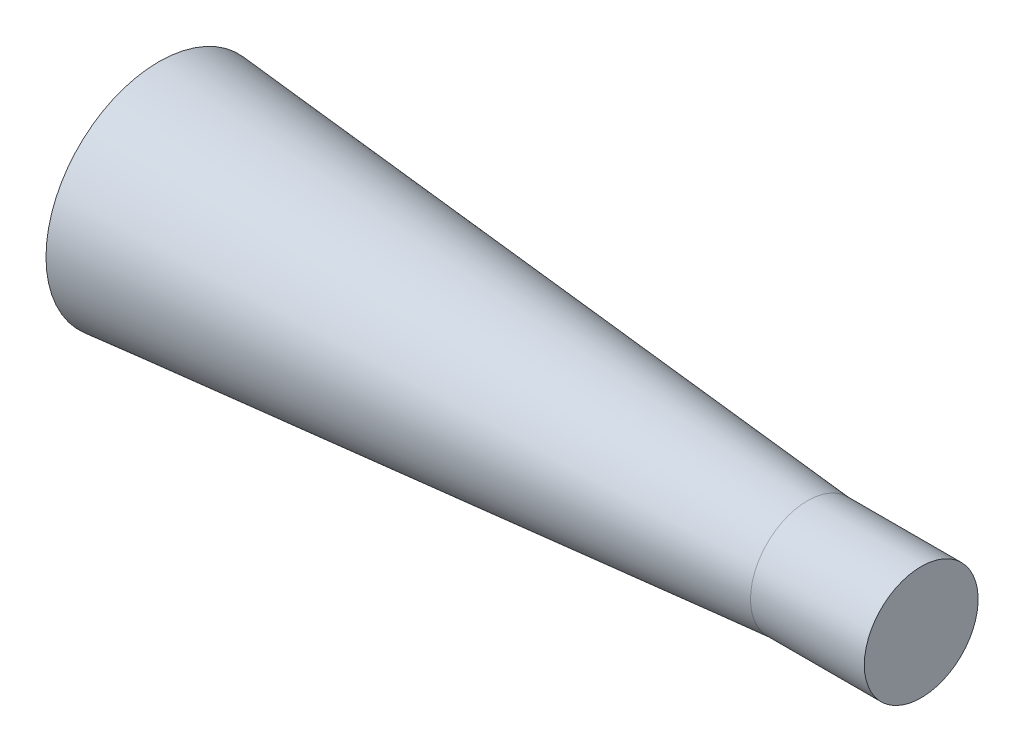
SolidWorks part; units mm, degrees
ref_plane "Front Plane" through (0, 0, 0) normal (0, 0, 1) x (1, 0, 0)
ref_plane "Top Plane" through (0, 0, 0) normal (0, 1, 0) x (1, 0, 0)
ref_plane "Right Plane" through (0, 0, 0) normal (1, 0, 0) x (0, 0, -1)
sketch "Sketch1" plane through (0, 0, 0) normal (0, 0, 1) x (1, 0, 0)
  line L0 (0, 0) -> (34, 0) construction
  line L1 (29, 2.5) -> (0, 5)
  line L2 (29, 2.5) -> (34, 2.5)
  line L3 (34, 2.5) -> (34, 0)
  line L4 (0, 5) -> (0, 0) construction
  line L5 (0, 0) -> (34, 0)
  arc A0 (0, 0) -> (0.5, 4.9569) centre (24.8208, 0) cw
  dimension "D1" = 34
  dimension "D2" = 5
  dimension "D3" = 10
  dimension "D4" = 5
  dimension "D5" = 0.5
revolve "Revolve1" add sketch "Sketch1" angle 360 about L0
